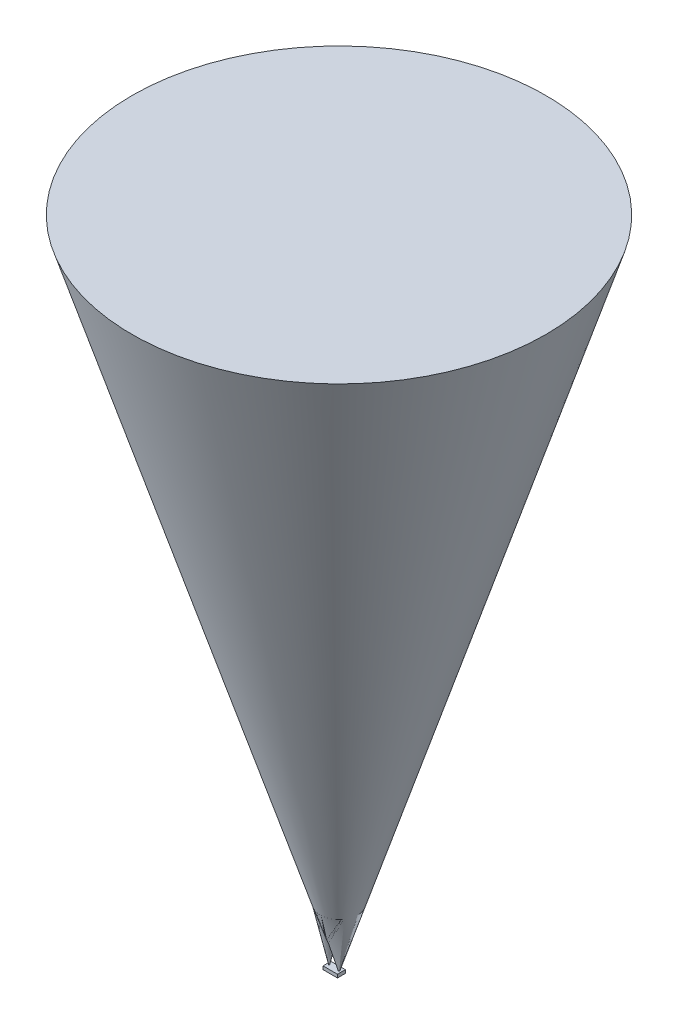
SolidWorks part; units mm, degrees
ref_plane "Front Plane" through (0, 0, 0) normal (0, 0, 1) x (1, 0, 0)
ref_plane "Top Plane" through (0, 0, 0) normal (0, 1, 0) x (1, 0, 0)
ref_plane "Right Plane" through (0, 0, 0) normal (1, 0, 0) x (0, 0, -1)
sketch "Sketch2" plane through (0, 0, 0) normal (0, 1, 0) x (1, 0, 0)
  line L0 (-1.535, 0) -> (1.465, 0) construction
  line L1 (-2.2, -1.2) -> (2.2, -1.2)
  line L2 (-2.2, -1.2) -> (-2.2, 1.2)
  line L3 (-2.2, 1.2) -> (2.2, 1.2)
  line L4 (2.2, -1.2) -> (2.2, 1.2)
  line L5 (-2.2, -1.2) -> (2.2, 1.2) construction
  line L6 (-2.2, 1.2) -> (2.2, -1.2) construction
  line L7 (-1.535, 0) -> (-2.2, 0) construction
  circle A0 centre (1.465, 0) radius 0.2
  circle A1 centre (-1.535, 0) radius 0.1
  point P0 (0, 0)
  dimension "D4" = 0.4
  dimension "D5" = 0.2
  dimension "D1" = 4.4
  dimension "D2" = 2.4
  dimension "D3" = 3
  dimension "D6" = 0.665
extrude "Boss-Extrude1" add sketch "Sketch2" along normal blind 1
sketch "Sketch3" plane through (0, 0, 0) normal (0, 0, 1) x (1, 0, 0)
  line L0 (-1.435, 1) -> (-1.635, 1) construction
  line L1 (-1.435, 1) -> (-1.635, 1) construction
  line L2 (-1.535, 0.5489) -> (-1.535, 200.5489)
  line L3 (-1.535, 200.5489) -> (42.8039, 200.5489)
  line L4 (42.8039, 200.5489) -> (-1.535, 0.5489)
  line L5 (-1.535, 0.5489) -> (-45.8739, 200.5489) construction
  line L6 (-45.8739, 200.5489) -> (-1.535, 200.5489) construction
  point P2 (-1.535, 1)
  dimension "D1" = 25
  dimension "D2" = 200
revolve "Revolve1" add sketch "Sketch3" angle 360 about L2
sketch "Sketch4" plane through (0, 0, 0) normal (0, 0, 1) x (1, 0, 0)
  line L2 (1.665, 1) -> (1.265, 1) construction
  line L3 (1.465, 0.3657) -> (64.5825, 200.5489)
  line L4 (1.465, 0.3657) -> (1.465, 200.5489)
  line L5 (1.465, 200.5489) -> (64.5825, 200.5489)
  line L6 (1.465, 200.5489) -> (-61.6525, 200.5489) construction
  line L7 (-61.6525, 200.5489) -> (1.465, 0.3657) construction
  line L8 (1.665, 1) -> (1.265, 1) construction
  line L9 (42.8039, 200.5489) -> (-45.8739, 200.5489) construction
  point P3 (0, 0)
  point P4 (0, 0)
  point P5 (1.465, 1)
  point P8 (0, 0)
  point P10 (0, 0)
  dimension "D2" = 35
revolve "Revolve2" add sketch "Sketch4" angle 360 about L4
sketch "Sketch5" plane through (0, 0, 0) normal (0, 0, 1) x (1, 0, 0)
  line L0 (-1.535, 1) -> (-1.535, 2001)
  line L1 (1.465, 1) -> (1.465, 2001)
  line L2 (1.465, 0.3657) -> (1.465, 200.5489) construction
  line L4 (-2.2, 1) -> (2.2, 1) construction
  line L5 (-1.535, 0.5489) -> (-1.535, 200.5489) construction
  point P6 (0, 0)
  point P7 (0, 0)
  point P8 (0, 0)
  dimension "D1" = 2000
